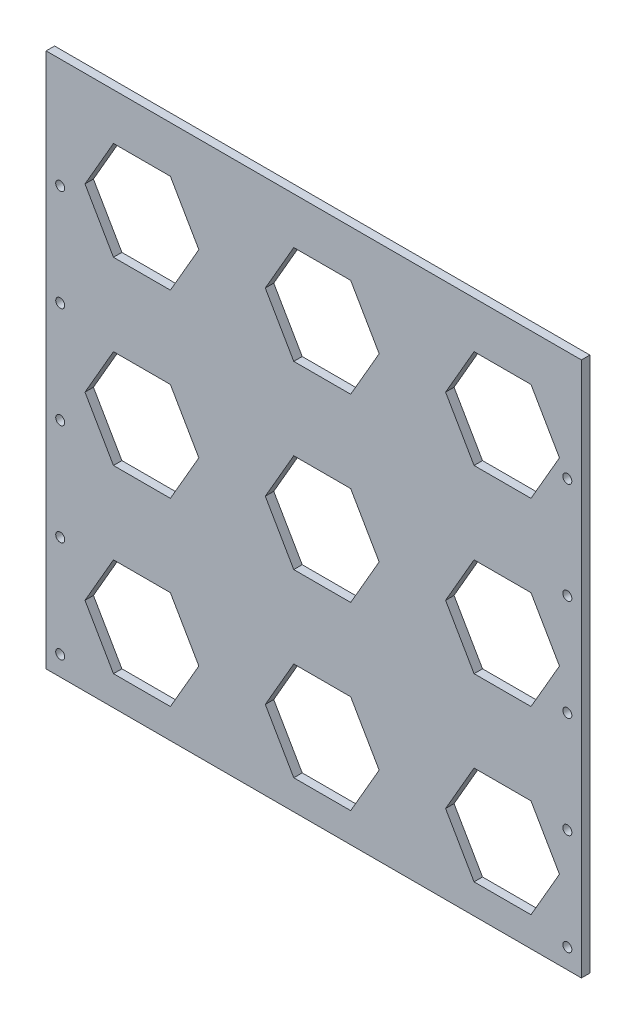
SolidWorks part; units mm, degrees
material "有机玻璃 (TM) GS 丙烯酸铸钣"
ref_plane "前视基准面" through (0, 0, 0) normal (0, 0, 1) x (1, 0, 0)
ref_plane "上视基准面" through (0, 0, 0) normal (0, 1, 0) x (1, 0, 0)
ref_plane "右视基准面" through (0, 0, 0) normal (1, 0, 0) x (0, 0, -1)
other "Configuration Table"
sketch "草图1" plane through (0, 0, 0) normal (0, 0, 1) x (1, 0, 0)
  line L1 (0, 0) -> (190, 0)
  line L2 (0, 0) -> (0, -190)
  line L3 (0, -190) -> (190, -190)
  line L4 (190, 0) -> (190, -190)
  dimension "D1" = 190
  dimension "D2" = 190
extrude "凸台-拉伸1" add sketch "草图1" along normal blind 3
sketch "草图2" plane through (0, 0, 3) normal (0, 0, 1) x (1, 0, 0)
  line L0 (0, 0) -> (0, -190) construction
  line L1 (54.2073, -34) -> (44.1036, -16.5)
  line L2 (44.1036, -16.5) -> (23.8964, -16.5)
  line L3 (23.8964, -16.5) -> (13.7927, -34)
  line L4 (13.7927, -34) -> (23.8964, -51.5)
  line L5 (23.8964, -51.5) -> (44.1036, -51.5)
  line L6 (44.1036, -51.5) -> (54.2073, -34)
  line L7 (190, 0) -> (0, 0) construction
  line L8 (108.1036, -16.5) -> (87.8964, -16.5)
  line L9 (87.8964, -16.5) -> (77.7927, -34)
  line L10 (77.7927, -34) -> (87.8964, -51.5)
  line L11 (87.8964, -51.5) -> (108.1036, -51.5)
  line L12 (108.1036, -51.5) -> (118.2073, -34)
  line L13 (118.2073, -34) -> (108.1036, -16.5)
  line L14 (172.1036, -16.5) -> (151.8964, -16.5)
  line L15 (151.8964, -16.5) -> (141.7927, -34)
  line L16 (141.7927, -34) -> (151.8964, -51.5)
  line L17 (151.8964, -51.5) -> (172.1036, -51.5)
  line L18 (172.1036, -51.5) -> (182.2073, -34)
  line L19 (182.2073, -34) -> (172.1036, -16.5)
  line L32 (108.1036, -80.5) -> (87.8964, -80.5)
  line L33 (87.8964, -80.5) -> (77.7927, -98)
  line L34 (77.7927, -98) -> (87.8964, -115.5)
  line L35 (87.8964, -115.5) -> (108.1036, -115.5)
  line L36 (108.1036, -115.5) -> (118.2073, -98)
  line L37 (118.2073, -98) -> (108.1036, -80.5)
  line L38 (172.1036, -80.5) -> (151.8964, -80.5)
  line L39 (151.8964, -80.5) -> (141.7927, -98)
  line L40 (141.7927, -98) -> (151.8964, -115.5)
  line L41 (151.8964, -115.5) -> (172.1036, -115.5)
  line L42 (172.1036, -115.5) -> (182.2073, -98)
  line L43 (182.2073, -98) -> (172.1036, -80.5)
  line L56 (108.1036, -144.5) -> (87.8964, -144.5)
  line L57 (87.8964, -144.5) -> (77.7927, -162)
  line L58 (77.7927, -162) -> (87.8964, -179.5)
  line L59 (87.8964, -179.5) -> (108.1036, -179.5)
  line L60 (108.1036, -179.5) -> (118.2073, -162)
  line L61 (118.2073, -162) -> (108.1036, -144.5)
  line L62 (172.1036, -144.5) -> (151.8964, -144.5)
  line L63 (151.8964, -144.5) -> (141.7927, -162)
  line L64 (141.7927, -162) -> (151.8964, -179.5)
  line L65 (151.8964, -179.5) -> (172.1036, -179.5)
  line L66 (172.1036, -179.5) -> (182.2073, -162)
  line L67 (182.2073, -162) -> (172.1036, -144.5)
  line L200 (44.1036, -80.5) -> (23.8964, -80.5)
  line L201 (23.8964, -80.5) -> (13.7927, -98)
  line L202 (13.7927, -98) -> (23.8964, -115.5)
  line L203 (23.8964, -115.5) -> (44.1036, -115.5)
  line L204 (44.1036, -115.5) -> (54.2073, -98)
  line L205 (54.2073, -98) -> (44.1036, -80.5)
  line L206 (44.1036, -144.5) -> (23.8964, -144.5)
  line L207 (23.8964, -144.5) -> (13.7927, -162)
  line L208 (13.7927, -162) -> (23.8964, -179.5)
  line L209 (23.8964, -179.5) -> (44.1036, -179.5)
  line L210 (44.1036, -179.5) -> (54.2073, -162)
  line L211 (54.2073, -162) -> (44.1036, -144.5)
  line L242 (23.8964, -16.5) -> (23.8964, -433.5) construction
  circle A0 centre (34, -34) radius 17.5 construction
  dimension "D1" = 35
  dimension "D2" = 34
  dimension "D3" = 34
  dimension "D4" = 3
  dimension "D6" = 64
  dimension "D7" = 64
  dimension "D5" = 3
extrude "切除-拉伸1" cut sketch "草图2" against normal blind 3
sketch "草图3" plane through (0, 0, 3) normal (0, 0, 1) x (1, 0, 0)
  line L0 (44.1036, -80.5) -> (23.8964, -80.5) construction
  line L1 (0, 0) -> (0, -190) construction
  line L2 (190, -190) -> (190, 0) construction
  circle A0 centre (5, -75) radius 1.6
  circle A1 centre (185, -75) radius 1.6
  circle A2 centre (5, -111) radius 1.6
  circle A3 centre (185, -111) radius 1.6
  circle A4 centre (5, -147) radius 1.6
  circle A5 centre (185, -147) radius 1.6
  circle A6 centre (5, -183) radius 1.6
  circle A7 centre (185, -183) radius 1.6
  circle A10 centre (5, -39) radius 1.6
  circle A11 centre (185, -39) radius 1.6
  dimension "D1" = 3.2
  dimension "D8" = 36
  dimension "D9" = 36
  dimension "D11" = 5
  dimension "D2" = 5.5
  dimension "D3" = 5
  dimension "D6" = 180
  dimension "D7" = 36
  dimension "D10" = 5
  dimension "D4" = 2
  dimension "D5" = 4
extrude "切除-拉伸2" cut sketch "草图3" against normal blind 10
